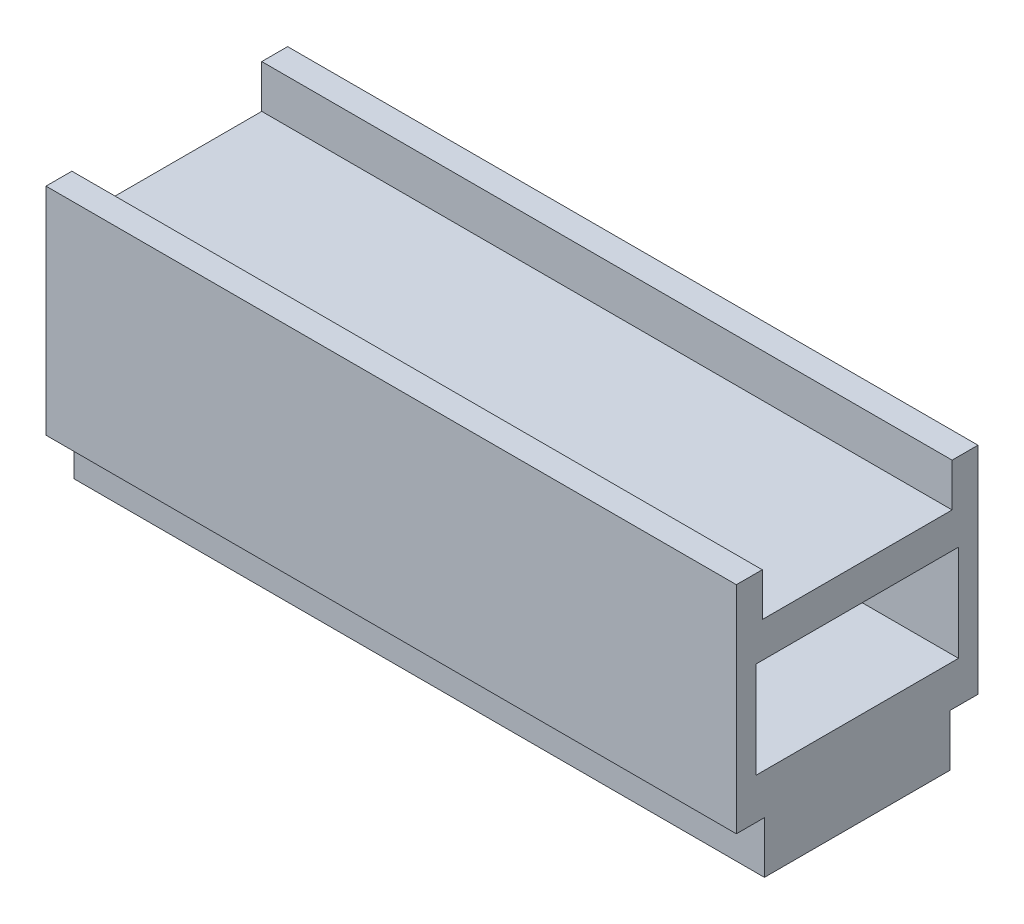
SolidWorks part; units mm, degrees
ref_plane "Front Plane" through (0, 0, 0) normal (0, 0, 1) x (1, 0, 0)
ref_plane "Top Plane" through (0, 0, 0) normal (0, 1, 0) x (1, 0, 0)
ref_plane "Right Plane" through (0, 0, 0) normal (1, 0, 0) x (0, 0, -1)
sketch "Sketch1" plane through (0, 0, 0) normal (0, 1, 0) x (1, 0, 0)
  line L1 (-40, 10.75) -> (40, 10.75)
  line L2 (-40, 10.75) -> (-40, -10.75)
  line L3 (-40, -10.75) -> (40, -10.75)
  line L4 (40, 10.75) -> (40, -10.75)
  line L5 (-40, 10.75) -> (40, -10.75) construction
  line L6 (-40, -10.75) -> (40, 10.75) construction
  point P0 (0, 0)
  dimension "D1" = 21.5
  dimension "D2" = 80
extrude "Boss-Extrude1" add sketch "Sketch1" along normal blind 6
sketch "Sketch2" plane through (0, 6, 0) normal (0, 1, 0) x (1, 0, 0)
  line L1 (-40, 14) -> (40, 14)
  line L2 (-40, 14) -> (-40, -14)
  line L3 (-40, -14) -> (40, -14)
  line L4 (40, 14) -> (40, -14)
  line L5 (-40, 14) -> (40, -14) construction
  line L6 (-40, -14) -> (40, 14) construction
  point P0 (0, 0)
  dimension "D1" = 80
  dimension "D2" = 28
extrude "Boss-Extrude2" add sketch "Sketch2" along normal blind 25
sketch "Sketch3" plane through (0, 31, 0) normal (0, 1, 0) x (1, 0, 0)
  line L0 (40, -14) -> (40, 14) construction
  line L1 (-40, 11) -> (40, 11)
  line L2 (-40, 11) -> (-40, -11)
  line L3 (-40, -11) -> (40, -11)
  line L4 (40, 11) -> (40, -11)
  line L5 (-40, 11) -> (40, -11) construction
  line L6 (-40, -11) -> (40, 11) construction
  point P0 (0, 0)
  dimension "D1" = 22
extrude "Cut-Extrude1" cut sketch "Sketch3" against normal blind 5
sketch "Sketch4" plane through (40, 0, 0) normal (1, 0, 0) x (0, 0, -1)
  line L1 (-11.7434, 21.9007) -> (11.7434, 21.9007)
  line L2 (-11.7434, 21.9007) -> (-11.7434, 10.7375)
  line L3 (-11.7434, 10.7375) -> (11.7434, 10.7375)
  line L4 (11.7434, 21.9007) -> (11.7434, 10.7375)
  line L5 (-11.7434, 21.9007) -> (11.7434, 10.7375) construction
  line L6 (-11.7434, 10.7375) -> (11.7434, 21.9007) construction
  point P0 (0, 16.3191)
  point P1 (0, 16.3191)
extrude "Cut-Extrude2" cut sketch "Sketch4" against normal up to next
